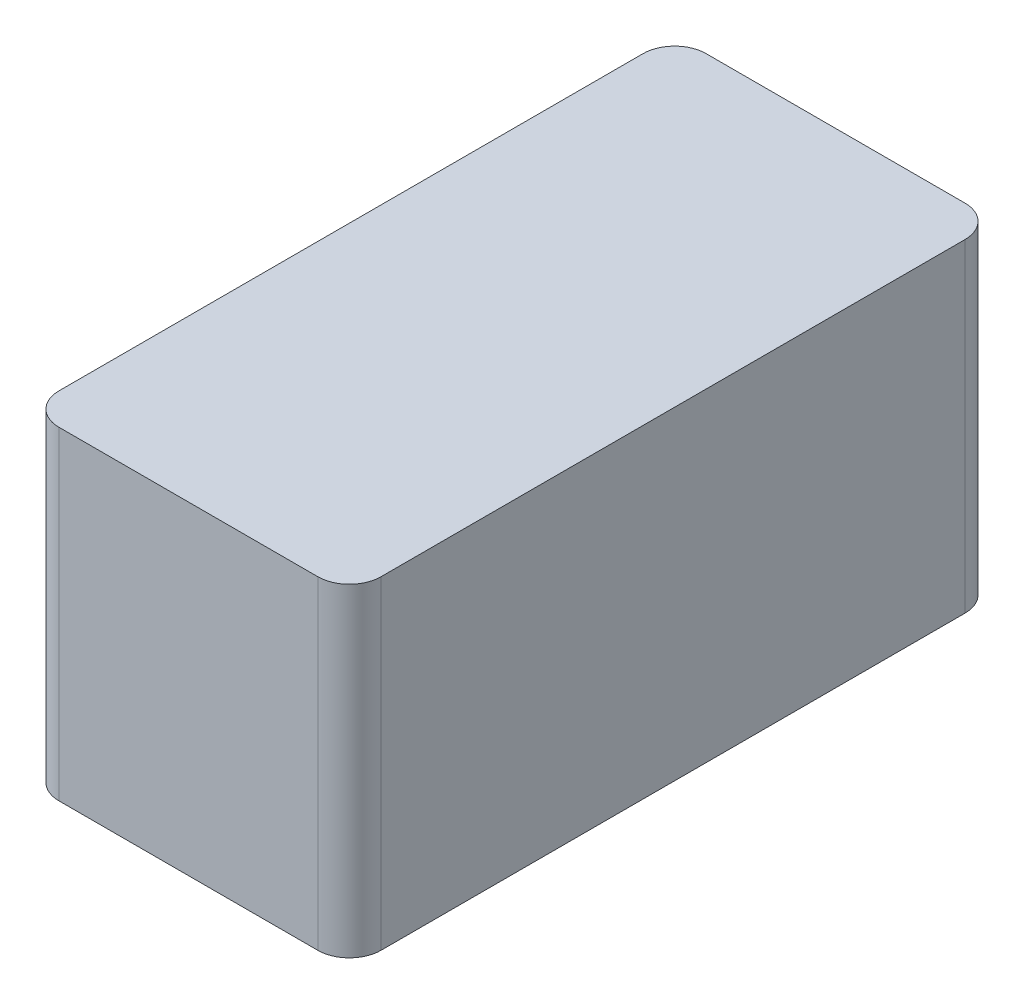
SolidWorks part; units mm, degrees
material "Polyethylene Cross-Linked"
ref_plane "Front Plane" through (0, 0, 0) normal (0, 0, 1) x (1, 0, 0)
ref_plane "Top Plane" through (0, 0, 0) normal (0, 1, 0) x (1, 0, 0)
ref_plane "Right Plane" through (0, 0, 0) normal (1, 0, 0) x (0, 0, -1)
sketch "Sketch1" plane through (0, 0, 0) normal (0, 1, 0) x (1, 0, 0)
  line L1 (-10.2, 20.5) -> (10.2, 20.5)
  line L2 (-10.2, 20.5) -> (-10.2, -20.5)
  line L3 (-10.2, -20.5) -> (10.2, -20.5)
  line L4 (10.2, 20.5) -> (10.2, -20.5)
  line L5 (-10.2, 20.5) -> (10.2, -20.5) construction
  line L6 (-10.2, -20.5) -> (10.2, 20.5) construction
  point P0 (0, 0)
  dimension "D1" = 20.4
  dimension "D2" = 41
extrude "Boss-Extrude1" add sketch "Sketch1" along normal mid plane 20.5
fillet "Fillet1" radius 2 4 edges at (-10.2, 0, -20.5) (10.2, 0, -20.5) (10.2, 0, 20.5) (-10.2, 0, 20.5)
